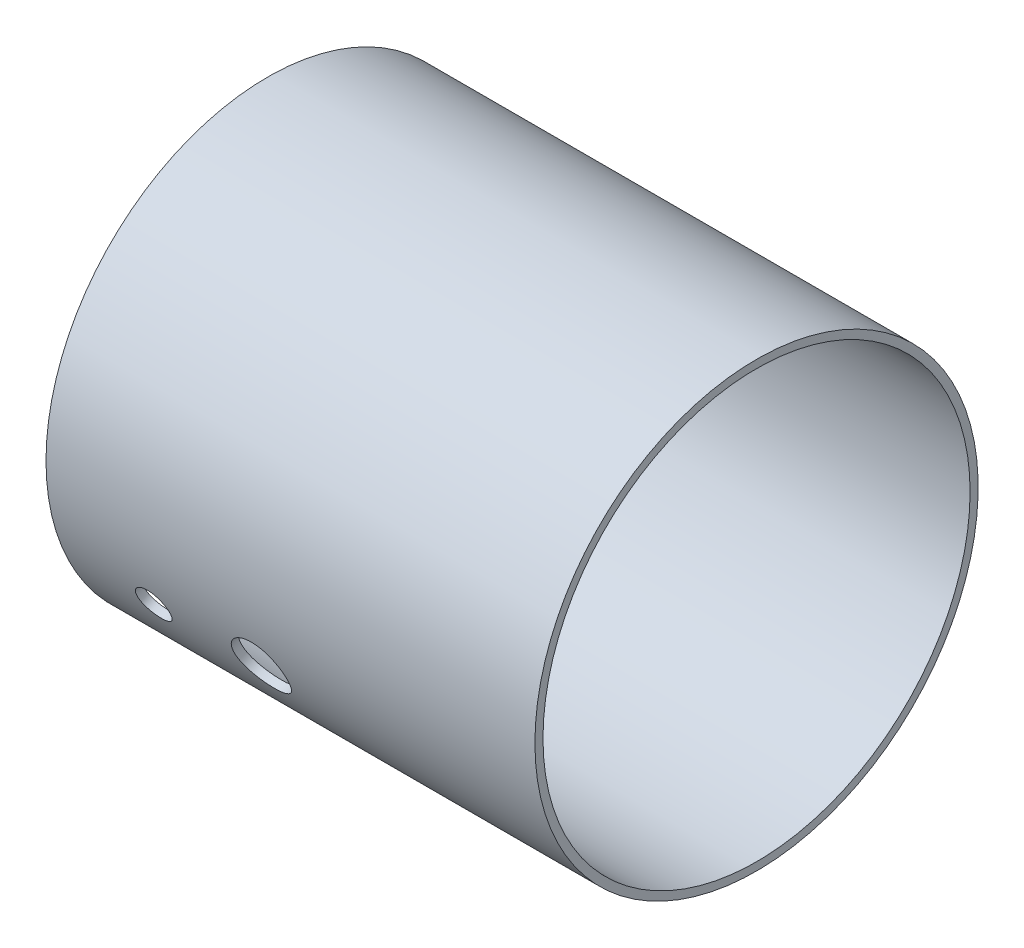
SolidWorks part; units mm, degrees
material "AISI 316 Stainless Steel Sheet (SS)"
ref_plane "Front Plane" through (0, 0, 0) normal (0, 0, 1) x (1, 0, 0)
ref_plane "Top Plane" through (0, 0, 0) normal (0, 1, 0) x (1, 0, 0)
ref_plane "Right Plane" through (0, 0, 0) normal (1, 0, 0) x (0, 0, -1)
sketch "Sketch1" plane through (0, 0, 0) normal (0, 0, 1) x (1, 0, 0)
  line L0 (-120.0179, 0) -> (5880.8787, 0) construction
  line L1 (182, 82.5) -> (182, 79.5)
  line L2 (0, 82.5) -> (182, 82.5)
  line L3 (0, 82.5) -> (0, 79.5)
  line L4 (0, 79.5) -> (182, 79.5)
  dimension "D1" = 3
  dimension "D3" = 82.5
  dimension "D7" = 182
revolve "Revolve1" add sketch "Sketch1" angle 360 about L0
sketch "Sketch2" plane through (91.82, -35.7463, -15.8629) normal (0, -0.4056, 0.914) x (1, 0, 0)
  circle A1 centre (-18.82, 39.1079) radius 10.4
  circle A2 centre (-58.82, 39.1079) radius 6.35
  dimension "D4" = 20.8
  dimension "D6" = 12.7
  dimension "D1" = 73
  dimension "D7" = 33
extrude "Cut-Extrude1" cut sketch "Sketch2" along normal up to surface (81.8419 mm away)
